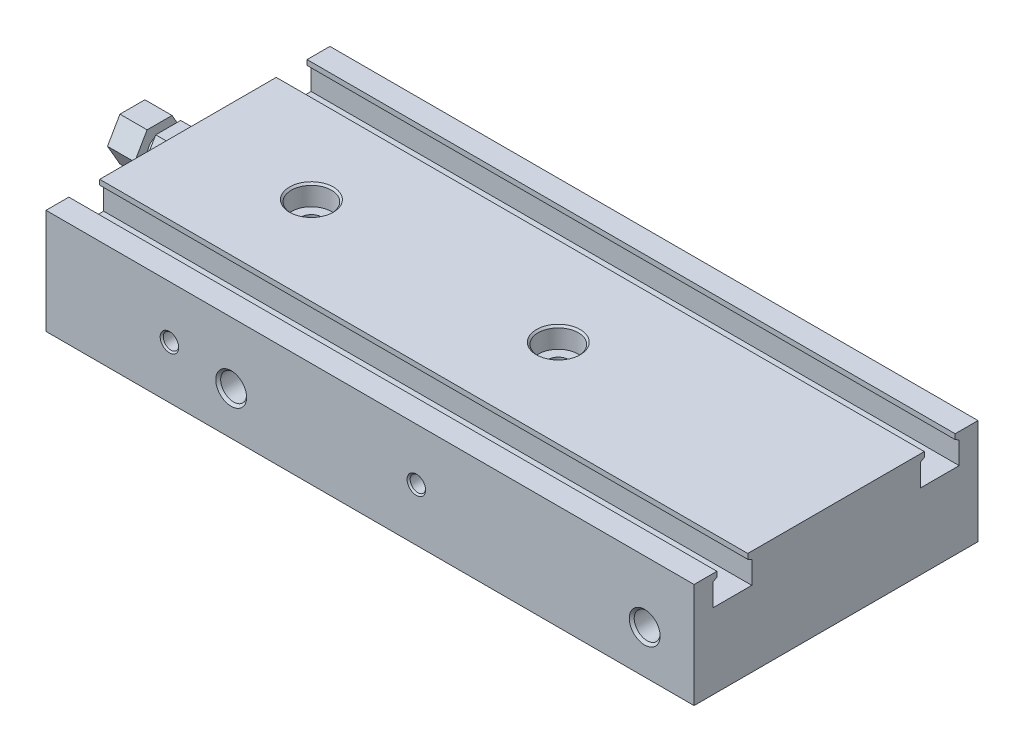
SolidWorks part; units mm, degrees
ref_plane "Plane1" through (0, 0, 0) normal (0, 0, 1) x (1, 0, 0)
ref_plane "Plane2" through (0, 0, 0) normal (0, 1, 0) x (1, 0, 0)
ref_plane "Plane3" through (0, 0, 0) normal (1, 0, 0) x (0, 0, -1)
sketch "Body_Sketch" plane through (0, 0, 0) normal (1, 0, 0) x (0, 0, -1)
  line L0 (-23, 10) -> (-23, -7)
  line L1 (-23, -7) -> (23, -7)
  line L2 (23, -7) -> (23, 10)
  line L3 (23, 10) -> (-23, 10)
  line L4 (-25.3, 0) -> (25.3, 0) construction
  line L5 (0, -7.85) -> (0, 10.85) construction
  line L6 (27.956, 0) -> (-27.956, 0) construction
  line L7 (0, 12.3416) -> (0, -12.3416) construction
  dimension "A" = 46
  dimension "B" = 17
  dimension "QQ" = 7
extrude "Body" add sketch "Body_Sketch" along normal blind 105
sketch "Body Bot Grooves_Sketch" [suppressed] plane through (0, 0, 0) normal (1, 0, 0) x (0, 0, -1)
  line L0 (0, 0) -> (0, -14.4793) construction
  line L1 (-12, -6.5) -> (-4, -6.5)
  line L2 (-4, -6.5) -> (-5, -5.5)
  line L3 (-5, -5.5) -> (-11, -5.5)
  line L4 (-11, -5.5) -> (-12, -6.5)
  line L5 (-8, -5.5) -> (-8, -12.5787) construction
  line L6 (18.5, 10) -> (-18.5, 10) construction
  line L7 (11, -5.5) -> (12, -6.5)
  line L8 (5, -5.5) -> (11, -5.5)
  line L9 (4, -6.5) -> (5, -5.5)
  line L10 (12, -6.5) -> (4, -6.5)
  dimension "Angle" = 45
  dimension "Raw Height" = 16.5
  dimension "Loc Y" = 15.5
  dimension "Width" = 8
  dimension "C2C" = 16
extrude "Body Bot Grooves" [suppressed] cut sketch "Body Bot Grooves_Sketch" along normal through all
sketch "Body Rod Holes_Sketch" plane through (0, 0, 0) normal (-1, 0, 0) x (0, 0, 1)
  line L0 (27.956, 0) -> (-27.956, 0) construction
  line L1 (0, 11.1009) -> (0, -8.2638) construction
  line L2 (0, -12.3416) -> (0, 12.3416) construction
  circle A0 centre (-10, 0) radius 3
  circle A1 centre (10, 0) radius 3
  dimension "NN" = 6
  dimension "H" = 20
extrude "Body Rod Holes" cut sketch "Body Rod Holes_Sketch" against normal blind 10
sketch "Body Piston Holes_Sketch" plane through (10, 0, 0) normal (-1, 0, 0) x (0, 0, 1)
  circle A0 centre (10, 0) radius 4.05
  circle A1 centre (-10, 0) radius 4.05
extrude "Body Piston Holes" cut sketch "Body Piston Holes_Sketch" against normal blind 51
sketch "Body Thru Hole_Sketch" [suppressed] plane through (0, 0, 0) normal (1, 0, 0) x (0, 0, -1)
  line L0 (0, 0) -> (0, -9.4152) construction
  line L1 (11.5, -6) -> (18.5, -6) construction
  circle A0 centre (14.95, -3) radius 1.4
  dimension "Dia" = 2.8
  dimension "Loc Y" = 3
  dimension "Loc Z" = 14.95
extrude "Body Thru Hole" [suppressed] cut sketch "Body Thru Hole_Sketch" along normal through all
sketch "Bot Switch Groove_Sketch" [suppressed] plane through (0, 0, 0) normal (1, 0, 0) x (0, 0, -1)
  line L0 (0, 0) -> (0, -12.0384) construction
  line L1 (1.6, -6.5) -> (-1.6, -6.5)
  line L2 (-1.6, -6.5) -> (-1.6, -3)
  line L3 (-1.6, -3) -> (-2.8, -3)
  line L4 (-2.8, -3) -> (-2.8, 0)
  line L5 (-2.8, 0) -> (2.8, 0)
  line L6 (2.8, -3) -> (2.8, 0)
  line L7 (-12, -6.5) -> (-4, -6.5) construction
  line L8 (1.6, -3) -> (2.8, -3)
  line L10 (1.6, -6.5) -> (1.6, -3)
  point P12 (0, 0)
  point P15 (0, -6.5)
  dimension "Bot Height" = 3.5
  dimension "Top Height" = 3
  dimension "Bot Width" = 3.2
  dimension "Top Width" = 5.6
extrude "Bot Switch Groove" [suppressed] cut sketch "Bot Switch Groove_Sketch" along normal through all
sketch "Top Switch Grooves_Sketch" plane through (0, 0, 0) normal (-1, 0, 0) x (0, 0, 1)
  line L0 (0, -12.3416) -> (0, 12.3416) construction
  line L1 (16.8, 4.6906) -> (16.8, 11.0706) construction
  line L2 (-23, 10) -> (23, 10) construction
  line L3 (13.65, 5.2) -> (19.95, 5.2)
  line L4 (-13.65, 8.8) -> (-13.65, 5.2)
  line L5 (-13.65, 5.2) -> (-19.95, 5.2)
  line L6 (-19.95, 5.2) -> (-19.95, 8.8)
  line L7 (-19.3, 10) -> (-14.3, 10)
  line L8 (19.95, 5.2) -> (19.95, 8.8)
  line L9 (19.3, 9.1753) -> (19.95, 8.8)
  line L10 (19.3, 10) -> (19.3, 9.1753)
  line L11 (19.3, 10) -> (14.3, 10)
  line L12 (-19.3, 10) -> (-19.3, 9.1753)
  line L13 (-14.3, 10) -> (-14.3, 9.1753)
  line L14 (-14.3, 9.1753) -> (-13.65, 8.8)
  line L15 (-19.3, 9.1753) -> (-19.95, 8.8)
  line L16 (0, 4.91) -> (0, 11.29) construction
  line L17 (14.3, 10) -> (14.3, 9.1753)
  line L18 (-16.8, 4.91) -> (-16.8, 11.29) construction
  line L19 (14.3, 9.1753) -> (13.65, 8.8)
  line L20 (13.65, 8.8) -> (13.65, 5.2)
  point P4 (-16.8, 10)
  point P12 (16.8, 10)
  dimension "Bot Width" = 6.3
  dimension "Top Width" = 5
  dimension "P" = 33.6
  dimension "Bot Height" = 3.6
  dimension "Angle" = 120
  dimension "Depth" = 4.8
extrude "Top Switch Grooves" cut sketch "Top Switch Grooves_Sketch" against normal through all
sketch "SHCS MGT Hole_Sketch" plane through (0, 0, 0) normal (0, 0, 1) x (1, 0, 0)
  line L0 (20, 10) -> (16.75, 10)
  line L1 (16.75, 10) -> (16.75, 6.7)
  line L2 (16.75, 6.7) -> (18.3, 6.7)
  line L3 (18.3, 6.7) -> (18.3, -7)
  line L4 (18.3, -7) -> (20, -7)
  line L5 (20, -7) -> (20, 10)
  line L6 (20, -11.5069) -> (20, 12.6548) construction
  line L7 (105, 10) -> (0, 10) construction
  line L8 (105, -7) -> (0, -7) construction
  line L9 (0, -12.5712) -> (0, 12.5712) construction
  dimension "M_depth" = 3.3
  dimension "M" = 6.5
  dimension "U" = 3.4
  dimension "L" = 20
revolve "SHCS MGT Hole" cut sketch "SHCS MGT Hole_Sketch" angle 360 about L6
chamfer "SHCS MGT Hole Cham" distance 0.3 1 edges at (20, 10, -3.25)
pattern_linear "SHCS MGT Hole Pat" count 2 spacing 40 along (1, 0, 0) of "SHCS MGT Hole", "SHCS MGT Hole Cham"
hole_wizard "SHCS MGT Hole Bot Tap" positions "SHCS MGT Hole Bot Tap Loc" profile "SHCS MGT Hole Bot Tap Profile" tap size "M4x0.7" standard "Ansi Metric"
sketch "SHCS MGT Hole Bot Tap Loc" plane through (0, -7, 0) normal (0, -1, 0) x (1, 0, 0)
  circle A0 centre (60, 0) radius 1.7 construction
  circle A1 centre (20, 0) radius 1.7 construction
  point P0 (20, 0)
  point P1 (60, 0)
sketch "SHCS MGT Hole Bot Tap Profile" plane through (20, -7, 0) normal (1, 0, 0) x (0, 0, -1)
  line L0 (0, 0) -> (0, 9.0215)
  line L1 (0, 9.0215) -> (1.7, 8)
  line L2 (1.7, 8) -> (1.7, 7)
  line L3 (1.7, 7) -> (2, 7)
  line L5 (2, 7) -> (2, 0.3)
  line L6 (2, 0.3) -> (2.3, 0)
  line L7 (2.3, 0) -> (0, 0)
  line L8 (-2, 0.3) -> (-2.3, 0) construction
  line L10 (0, 9.0215) -> (-1.7, 8) construction
  line L11 (0, -6.35) -> (0, 107.95) construction
  dimension "Tap Drill Dia." = 3.4
  dimension "Tap Drill Depth" = 8
  dimension "Thread Major Dia." = 4
  dimension "Thread Depth" = 7
  dimension "Near CSink Dia." = 4.6
  dimension "Near CSink Angle" = 90
  dimension "Drill Angle" = 118
sketch "Adjuster Nut_Sketch" plane through (0, 0, 0) normal (-1, 0, 0) x (0, 0, 1)
  line L0 (-2.0207, 8.5) -> (2.0207, 8.5)
  line L1 (2.0207, 8.5) -> (4.0415, 5)
  line L2 (2.0207, 1.5) -> (4.0415, 5)
  line L3 (2.0207, 1.5) -> (-2.0207, 1.5)
  line L4 (-4.0415, 5) -> (-2.0207, 1.5)
  line L5 (-2.0207, 8.5) -> (-4.0415, 5)
  line L6 (0, -12.3416) -> (0, 12.3416) construction
  line L7 (27.956, 0) -> (-27.956, 0) construction
  line L8 (-4.4456, 5) -> (4.4456, 5) construction
  line L10 (0, 1.15) -> (0, 8.85) construction
  circle A0 centre (0, 5) radius 3.5 construction
  dimension "OO_keyw" = 7
  dimension "TT" = 5
extrude "Adjuster Nut" add sketch "Adjuster Nut_Sketch" along normal blind 9
sketch "Adjuster Nut Threads_Sketch" plane through (0, 0, 0) normal (0, 0, 1) x (1, 0, 0)
  line L0 (-4.6, 24) -> (-4.6, 7)
  line L1 (-4.6, 7) -> (-3.2, 7)
  line L2 (-3.2, 7) -> (-3.2, 24)
  line L3 (-3.2, 24) -> (-4.6, 24)
  line L4 (-6.476, 5) -> (-3.044, 5) construction
  line L5 (-9, 5) -> (0, 5) construction
  line L6 (0, -12.5712) -> (0, 12.5712) construction
  line L7 (-9, 5) -> (-9, 8.5) construction
  line L8 (0, 10) -> (0, -7) construction
  dimension "OO" = 4
  dimension "Nut Thickness Body" = 3.2
  dimension "Nut Thickness Plate" = 4.4
revolve "Adjuster Nut Threads" cut sketch "Adjuster Nut Threads_Sketch" angle 360 about L4
hole_wizard "Tap Drill for M5x0.8 Tap1" positions "Sketch2" profile "Sketch1" hole size "M5x0.8" standard "ANSI Metric"
sketch "Sketch2" plane through (0, 0, 23) normal (0, 0, 1) x (1, 0, 0)
  line L0 (105, -7) -> (0, -7) construction
  line L1 (105, 10) -> (105, -7) construction
  line L2 (0, 10) -> (0, -7) construction
  point P0 (30, 0)
  point P2 (97, 0)
  dimension "D1" = 7
  dimension "D2" = 8
  dimension "D3" = 30
sketch "Sketch1" plane through (30, 0, 23) normal (1, 0, 0) x (0, -1, 0)
  line L0 (0, 0) -> (0, 5.7618)
  line L1 (0, 5.7618) -> (2.1, 4.5)
  line L2 (2.1, 4.5) -> (2.1, 0.4)
  line L3 (2.1, 0.4) -> (2.5, 0)
  line L5 (2.5, 0) -> (0, 0)
  line L6 (-2.1, 0.4) -> (-2.5, 0) construction
  line L10 (0, 5.7618) -> (-2.1, 4.5) construction
  line L11 (0, -6.35) -> (0, 107.95) construction
  dimension "Hole Dia." = 4.2
  dimension "Hole Depth" = 4.5
  dimension "Near C'Sink Dia." = 5
  dimension "Near C'Sink Angle" = 90
  dimension "Drill Angle" = 118
hole_wizard "Tap Drill for M5x0.8 Tap2" positions "Sketch4" profile "Sketch3" hole size "M5x0.8" standard "ANSI Metric"
sketch "Sketch4" plane through (0, 0, -23) normal (0, 0, -1) x (-1, 0, 0)
  line L0 (-105, -7) -> (-105, 10) construction
  line L1 (0, -7) -> (0, 10) construction
  line L2 (-105, -7) -> (0, -7) construction
  point P0 (-97, 0)
  point P2 (-30, 0)
  dimension "D1" = 8
  dimension "D2" = 30
  dimension "D3" = 7
sketch "Sketch3" plane through (97, 0, -23) normal (1, 0, 0) x (0, 1, 0)
  line L0 (0, 0) -> (0, 5.7618)
  line L1 (0, 5.7618) -> (2.1, 4.5)
  line L2 (2.1, 4.5) -> (2.1, 0.4)
  line L3 (2.1, 0.4) -> (2.5, 0)
  line L5 (2.5, 0) -> (0, 0)
  line L6 (-2.1, 0.4) -> (-2.5, 0) construction
  line L10 (0, 5.7618) -> (-2.1, 4.5) construction
  line L11 (0, -6.35) -> (0, 107.95) construction
  dimension "Hole Dia." = 4.2
  dimension "Hole Depth" = 4.5
  dimension "Near C'Sink Dia." = 5
  dimension "Near C'Sink Angle" = 90
  dimension "Drill Angle" = 118
hole_wizard "Mount_Holes_1" positions "Sketch6" profile "Sketch5" hole size "M3x0.5" standard "ANSI Metric"
sketch "Sketch6" plane through (0, 0, 23) normal (0, 0, 1) x (1, 0, 0)
  line L0 (105, -7) -> (0, -7) construction
  line L1 (0, 10) -> (0, -7) construction
  point P0 (20, 1.5)
  point P2 (60, 1.5)
  dimension "D1" = 8.5
  dimension "D2" = 20
  dimension "D3" = 40
sketch "Sketch5" plane through (20, 1.5, 23) normal (1, 0, 0) x (0, -1, 0)
  line L0 (0, 0) -> (0, 5.2511)
  line L1 (0, 5.2511) -> (1.25, 4.5)
  line L2 (1.25, 4.5) -> (1.25, 0.25)
  line L3 (1.25, 0.25) -> (1.5, 0)
  line L5 (1.5, 0) -> (0, 0)
  line L6 (-1.25, 0.25) -> (-1.5, 0) construction
  line L10 (0, 5.2511) -> (-1.25, 4.5) construction
  line L11 (0, -6.35) -> (0, 107.95) construction
  dimension "Hole Dia." = 2.5
  dimension "Hole Depth" = 4.5
  dimension "Near C'Sink Dia." = 3
  dimension "Near C'Sink Angle" = 90
  dimension "Drill Angle" = 118
hole_wizard "Mount_Holes_2" positions "Sketch8" profile "Sketch7" hole size "M3x0.5" standard "ANSI Metric"
sketch "Sketch8" plane through (0, 0, -23) normal (0, 0, -1) x (-1, 0, 0)
  line L0 (-105, -7) -> (0, -7) construction
  line L1 (0, -7) -> (0, 10) construction
  point P0 (-60, 1.5)
  point P2 (-20, 1.5)
  dimension "D1" = 8.5
  dimension "D2" = 20
  dimension "D3" = 40
sketch "Sketch7" plane through (60, 1.5, -23) normal (1, 0, 0) x (0, 1, 0)
  line L0 (0, 0) -> (0, 5.2511)
  line L1 (0, 5.2511) -> (1.25, 4.5)
  line L2 (1.25, 4.5) -> (1.25, 0.25)
  line L3 (1.25, 0.25) -> (1.5, 0)
  line L5 (1.5, 0) -> (0, 0)
  line L6 (-1.25, 0.25) -> (-1.5, 0) construction
  line L10 (0, 5.2511) -> (-1.25, 4.5) construction
  line L11 (0, -6.35) -> (0, 107.95) construction
  dimension "Hole Dia." = 2.5
  dimension "Hole Depth" = 4.5
  dimension "Near C'Sink Dia." = 3
  dimension "Near C'Sink Angle" = 90
  dimension "Drill Angle" = 118
hole_wizard "Mount_Holes_3" positions "Sketch10" profile "Sketch9" hole size "M4x0.7" standard "ANSI Metric"
sketch "Sketch10" plane through (0, 0, 49) normal (0, 0, 1) x (1, 0, 0)
  line L0 (182, 19) -> (0, 19) construction
  line L1 (0, 19) -> (0, -19) construction
  point P0 (30, 10)
  point P2 (100, 10)
  dimension "D1" = 7.75
  dimension "D2" = 30
  dimension "D3" = 30
sketch "Sketch9" plane through (30, 10, 49) normal (1, 0, 0) x (0, -1, 0)
  line L0 (0, 0) -> (0, 8.7618)
  line L1 (0, 8.7618) -> (2.1, 7.5)
  line L2 (2.1, 7.5) -> (2.1, 0.4)
  line L3 (2.1, 0.4) -> (2.5, 0)
  line L5 (2.5, 0) -> (0, 0)
  line L6 (-2.1, 0.4) -> (-2.5, 0) construction
  line L10 (0, 8.7618) -> (-2.1, 7.5) construction
  line L11 (0, -6.35) -> (0, 107.95) construction
  dimension "Hole Dia." = 3.3
  dimension "Hole Depth" = 5.5
  dimension "Near C'Sink Dia." = 4
  dimension "Near C'Sink Angle" = 90
  dimension "Drill Angle" = 118
hole_wizard "Mount_Holes_4" positions "Sketch12" profile "Sketch11" hole size "M4x0.7" standard "ANSI Metric"
sketch "Sketch12" plane through (0, 0, -49) normal (0, 0, -1) x (-1, 0, 0)
  line L1 (-182, 19) -> (0, 19) construction
  line L2 (0, -19) -> (0, 19) construction
  point P0 (-100, 10)
  point P2 (-30, 10)
  dimension "D1" = 7.75
  dimension "D2" = 30
  dimension "D3" = 30
sketch "Sketch11" plane through (100, 10, -49) normal (1, 0, 0) x (0, 1, 0)
  line L0 (0, 0) -> (0, 8.7618)
  line L1 (0, 8.7618) -> (2.1, 7.5)
  line L2 (2.1, 7.5) -> (2.1, 0.4)
  line L3 (2.1, 0.4) -> (2.5, 0)
  line L5 (2.5, 0) -> (0, 0)
  line L6 (-2.1, 0.4) -> (-2.5, 0) construction
  line L10 (0, 8.7618) -> (-2.1, 7.5) construction
  line L11 (0, -6.35) -> (0, 107.95) construction
  dimension "Hole Dia." = 3.3
  dimension "Hole Depth" = 5.5
  dimension "Near C'Sink Dia." = 4
  dimension "Near C'Sink Angle" = 90
  dimension "Drill Angle" = 118
hole_wizard "1/8 Rc Tapped Hole1" positions "Sketch14" profile "Sketch13" size "1/8" standard "ISO"
sketch "Sketch14" plane through (0, 0, 49) normal (0, 0, 1) x (1, 0, 0)
  line L0 (182, -19) -> (0, -19) construction
  line L1 (0, 19) -> (0, -19) construction
  line L2 (182, 19) -> (182, -19) construction
  point P0 (56, 0)
  point P2 (172, 0)
  dimension "D1" = 15
  dimension "D2" = 46
  dimension "D3" = 9
sketch "Sketch13" plane through (56, 0, 49) normal (1, 0, 0) x (0, -1, 0)
  line L0 (0, 0) -> (0, 11.4134)
  line L1 (3.95, 9.04) -> (0, 11.4134)
  line L2 (-3.95, 9.04) -> (0, 11.4134) construction
  line L3 (3.95, 9.04) -> (3.95, 4.5)
  line L4 (3.95, 4.5) -> (4.633, 4.5)
  line L5 (4.633, 4.5) -> (4.7735, 0)
  line L6 (-4.633, 4.5) -> (-4.7735, 0) construction
  line L7 (4.7735, 0) -> (0, 0)
  line L8 (0, -6.35) -> (0, 107.95) construction
  line L11 (-3.95, 4.5) -> (-4.633, 4.5) construction
  dimension "Tap Drill Dia." = 7.9
  dimension "Tap Drill Depth" = 9.04
  dimension "Thread Dia." = 9.5469
  dimension "Thread Angle" = 3.576
  dimension "Thread Depth" = 4.5
  dimension "Drill Angle" = 118
hole_wizard "1/8 Rc Tapped Hole2" positions "Sketch16" profile "Sketch15" size "1/8" standard "ISO"
sketch "Sketch16" plane through (0, 0, -49) normal (0, 0, -1) x (-1, 0, 0)
  line L0 (-182, -19) -> (0, -19) construction
  line L1 (0, -19) -> (0, 19) construction
  line L2 (-182, -19) -> (-182, 19) construction
  point P0 (-172, 0)
  point P2 (-56, 0)
  dimension "D1" = 15
  dimension "D2" = 46
  dimension "D3" = 9
sketch "Sketch15" plane through (172, 0, -49) normal (1, 0, 0) x (0, 1, 0)
  line L0 (0, 0) -> (0, 11.4134)
  line L1 (3.95, 9.04) -> (0, 11.4134)
  line L2 (-3.95, 9.04) -> (0, 11.4134) construction
  line L3 (3.95, 9.04) -> (3.95, 4.5)
  line L4 (3.95, 4.5) -> (4.633, 4.5)
  line L5 (4.633, 4.5) -> (4.7735, 0)
  line L6 (-4.633, 4.5) -> (-4.7735, 0) construction
  line L7 (4.7735, 0) -> (0, 0)
  line L8 (0, -6.35) -> (0, 107.95) construction
  line L11 (-3.95, 4.5) -> (-4.633, 4.5) construction
  dimension "Tap Drill Dia." = 7.9
  dimension "Tap Drill Depth" = 9.04
  dimension "Thread Dia." = 9.5469
  dimension "Thread Angle" = 3.576
  dimension "Thread Depth" = 4.5
  dimension "Drill Angle" = 118
